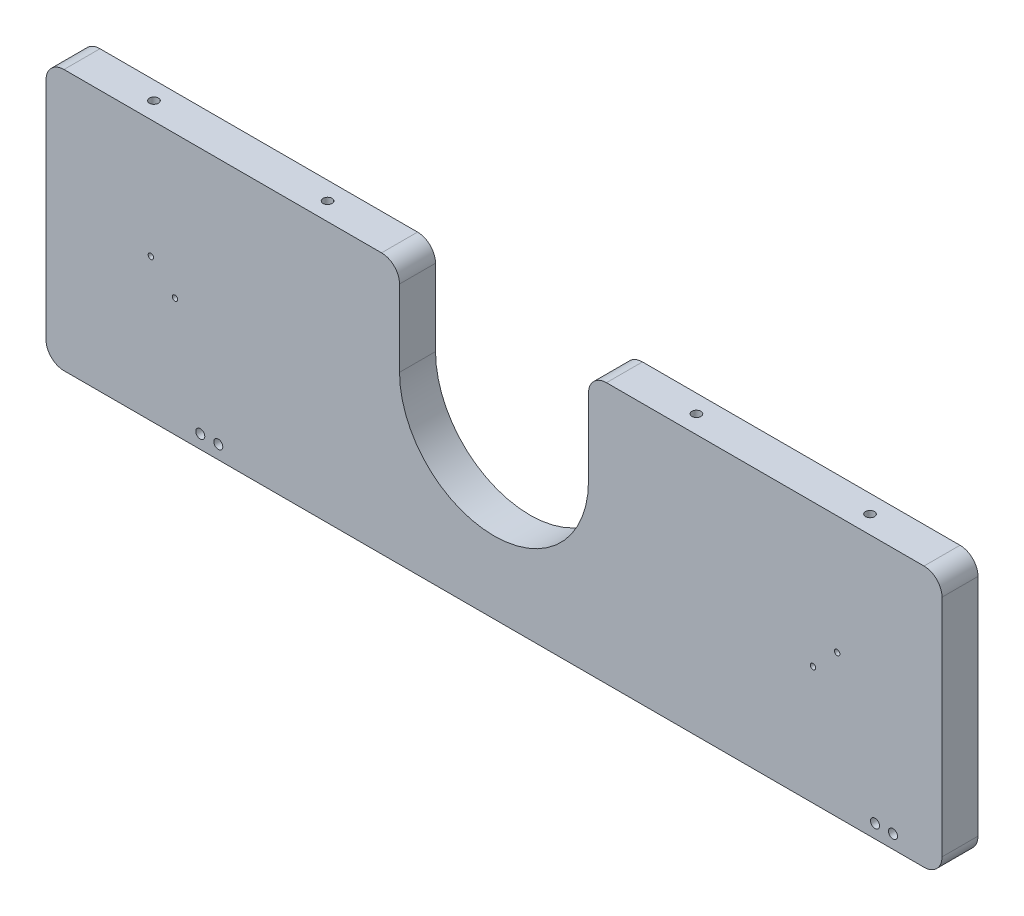
SolidWorks part; units mm, degrees
ref_plane "Ön Düzlem" through (0, 0, 0) normal (0, 0, 1) x (1, 0, 0)
ref_plane "Üst Düzlem" through (0, 0, 0) normal (0, 1, 0) x (1, 0, 0)
ref_plane "Sağ Düzlem" through (0, 0, 0) normal (1, 0, 0) x (0, 0, -1)
sketch "Sketch1" plane through (0, 0, 0) normal (0, 0, 1) x (1, 0, 0)
  line L0 (52.5, 20.7816) -> (249, 20.7816)
  line L1 (-249, -124.2184) -> (249, -124.2184)
  line L2 (-249, -124.2184) -> (-249, 20.7816)
  line L4 (249, -124.2184) -> (249, 20.7816)
  line L8 (-52.5, -31.7184) -> (-52.5, 20.7816)
  line L9 (-249, -116.7184) -> (249, -116.7184) construction
  line L10 (-249, 20.7816) -> (-52.5, 20.7816)
  line L11 (52.5, -31.7184) -> (52.5, 20.7816)
  circle A1 centre (-163.25, -116.7184) radius 2.5
  circle A2 centre (-153.25, -116.7184) radius 2.5
  circle A3 centre (211.75, -116.7184) radius 2.5
  circle A4 centre (221.75, -116.7184) radius 2.5
  arc A5 (-52.5, -31.7184) -> (52.5, -31.7184) centre (0, -31.7184) ccw
  point P0 (0, 0)
  dimension "D3" = 105
  dimension "D5" = 5
  dimension "D6" = 5
  dimension "D9" = 5
  dimension "D10" = 5
  dimension "D1" = 498
  dimension "D2" = 145
  dimension "D4" = 7.5
  dimension "D7" = 10
  dimension "D8" = 412.25
  dimension "D11" = 10
  dimension "D12" = 27.25
extrude "Boss-Extrude1" add sketch "Sketch1" along normal blind 20
fillet "Fillet1" radius 10 2 edges at (-249, -124.2184, 10) (249, -124.2184, 10)
sketch "Sketch2" plane through (0, 0, 20) normal (0, 0, 1) x (1, 0, 0)
  line L0 (-83.1983, 20.7816) -> (-83.1983, -124.2184) construction
  line L1 (-52.5, 20.7816) -> (-249, 20.7816) construction
  line L2 (-239, -124.2184) -> (239, -124.2184) construction
  line L3 (-83.1983, -51.7184) -> (-249, -51.7184) construction
  line L4 (-249, 20.7816) -> (-249, -114.2184) construction
  line L5 (-249, 13.2816) -> (-154.1423, -81.5761) construction
  line L6 (0, 0) -> (0, -64.9578) construction
  circle A0 centre (-177.2825, -58.4359) radius 1.5
  circle A1 centre (-190.7175, -45.0009) radius 1.5
  circle A2 centre (190.7175, -45.0009) radius 1.5
  circle A3 centre (177.2825, -58.4359) radius 1.5
  point P19 (-184, -51.7184)
  dimension "D3" = 3
  dimension "D4" = 3
  dimension "D1" = 45
  dimension "D2" = 65
  dimension "D5" = 19
  dimension "D6" = 9.5
extrude "Cut-Extrude1" cut sketch "Sketch2" against normal up to surface (20 mm away) up to face at (0, -51.3826, 0)
sketch "Sketch3" plane through (0, 20.7816, 0) normal (0, 1, 0) x (1, 0, 0)
  line L0 (-249, -10) -> (-52.5, -10) construction
  line L1 (-249, -20) -> (-249, 0) construction
  line L2 (-52.5, -20) -> (-52.5, 0) construction
  line L3 (0, 0) -> (0, -20) construction
  line L4 (-52.5, -20) -> (52.5, -20) construction
  line L5 (-52.5, -20) -> (-52.5, 0) construction
  circle A0 centre (-199, -10) radius 2.5
  circle A1 centre (-102.5, -10) radius 2.5
  circle A2 centre (102.5, -10) radius 2.5
  circle A3 centre (199, -10) radius 2.5
  dimension "D1" = 5
  dimension "D2" = 5
  dimension "D3" = 50
  dimension "D4" = 50
extrude "Cut-Extrude2" cut sketch "Sketch3" against normal blind 10
fillet "Fillet2" radius 10 4 edges at (249, 20.7816, 10) (-249, 20.7816, 10) (52.5, 20.7816, 10) (-52.5, 20.7816, 10)
